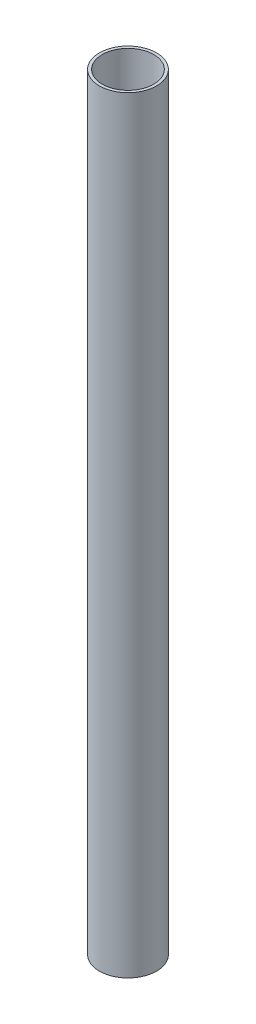
SolidWorks part; units mm, degrees
ref_plane "Front Plane" through (0, 0, 0) normal (0, 0, 1) x (1, 0, 0)
ref_plane "Top Plane" through (0, 0, 0) normal (0, 1, 0) x (1, 0, 0)
ref_plane "Right Plane" through (0, 0, 0) normal (1, 0, 0) x (0, 0, -1)
sketch "Sketch1" plane through (0, 0, 0) normal (0, 1, 0) x (1, 0, 0)
  circle A0 centre (0, 0) radius 10
  circle A1 centre (0, 0) radius 9
extrude "Boss-Extrude1" add sketch "Sketch1" along normal blind 268
